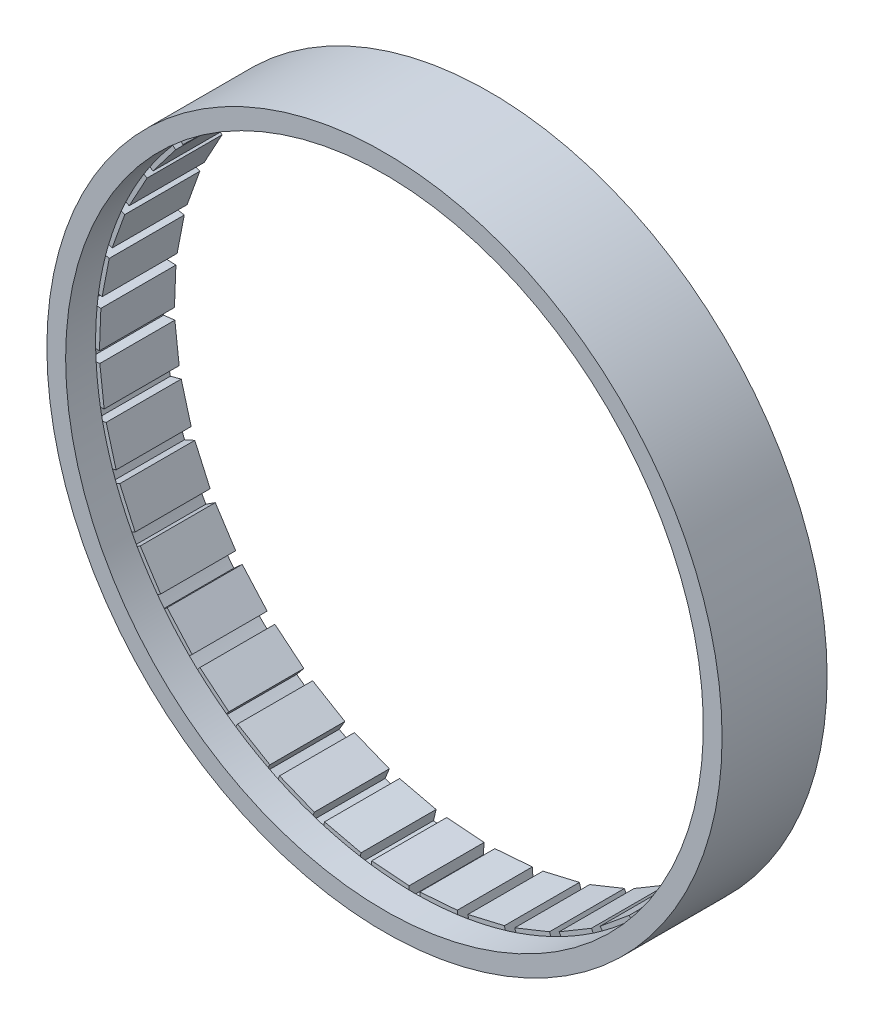
SolidWorks part; units mm, degrees
ref_plane "Front Plane" through (0, 0, 0) normal (0, 0, 1) x (1, 0, 0)
ref_plane "Top Plane" through (0, 0, 0) normal (0, 1, 0) x (1, 0, 0)
ref_plane "Right Plane" through (0, 0, 0) normal (1, 0, 0) x (0, 0, -1)
sketch "Sketch2" plane through (0, 0, 0) normal (1, 0, 0) x (0, 0, -1)
  line L0 (0, 0) -> (-98.2666, 0) construction
  line L1 (0, 45) -> (-14, 45)
  line L2 (-14, 45) -> (-14, 42.5)
  line L3 (-14, 42.5) -> (-10, 42.5)
  line L4 (-10, 42.5) -> (-10, 43.5)
  line L5 (-10, 43.5) -> (0, 43.5)
  line L6 (0, 43.5) -> (0, 45)
  point P5 (-13.7995, 43.5307)
  dimension "D1" = 90
  dimension "D2" = 85
  dimension "D3" = 14
  dimension "D4" = 4
  dimension "D5" = 1.5
revolve "Revolve1" add sketch "Sketch2" angle 360 about L0
sketch "Sketch4" plane through (0, 0, 0) normal (0, 0, -1) x (-1, 0, 0)
  line L0 (-2.5, 41.9281) -> (2.5, 41.9281)
  line L1 (2.5, 41.9281) -> (2.5, 43.4281)
  line L2 (-2.5, 41.9281) -> (-2.5, 43.4281)
  line L3 (3.9296, 41.8183) -> (4.1586, 43.3008)
  line L4 (8.871, 41.0551) -> (9.1, 42.5375)
  line L5 (3.9296, 41.8183) -> (8.871, 41.0551)
  line L6 (10.2671, 40.7284) -> (10.7197, 42.1585)
  line L7 (15.0341, 39.2198) -> (15.4866, 40.6499)
  line L8 (10.2671, 40.7284) -> (15.0341, 39.2198)
  line L9 (16.3639, 38.6838) -> (17.0295, 40.0281)
  line L10 (20.8447, 36.4652) -> (21.5103, 37.8095)
  line L11 (16.3639, 38.6838) -> (20.8447, 36.4652)
  line L12 (22.0772, 35.7325) -> (22.9402, 36.9594)
  line L13 (26.1668, 32.8559) -> (27.0298, 34.0828)
  line L14 (22.0772, 35.7325) -> (26.1668, 32.8559)
  line L15 (27.273, 31.9437) -> (28.3132, 33.0245)
  line L16 (30.8756, 28.4765) -> (31.9158, 29.5573)
  line L17 (27.273, 31.9437) -> (30.8756, 28.4765)
  line L18 (31.8296, 27.4061) -> (33.0225, 28.3155)
  line L19 (34.8607, 23.4296) -> (36.0536, 24.339)
  line L20 (31.8296, 27.4061) -> (34.8607, 23.4296)
  line L21 (35.6401, 22.2262) -> (36.9578, 22.9427)
  line L22 (38.0287, 17.8336) -> (39.3464, 18.5502)
  line L23 (35.6401, 22.2262) -> (38.0287, 17.8336)
  line L24 (38.6152, 16.5253) -> (40.0269, 17.0323)
  line L25 (40.3053, 11.8196) -> (41.717, 12.3266)
  line L26 (38.6152, 16.5253) -> (40.3053, 11.8196)
  line L27 (40.6852, 10.437) -> (42.1578, 10.7226)
  line L28 (41.6371, 5.5285) -> (43.1097, 5.8141)
  line L29 (40.6852, 10.437) -> (41.6371, 5.5285)
  line L30 (41.8016, 4.1041) -> (43.3005, 4.1616)
  line L31 (41.9931, -0.8922) -> (43.492, -0.8348)
  line L32 (41.8016, 4.1041) -> (41.9931, -0.8922)
  line L33 (41.9382, -2.325) -> (43.4283, -2.497)
  line L34 (41.3648, -7.292) -> (42.8549, -7.464)
  line L35 (41.9382, -2.325) -> (41.3648, -7.292)
  line L36 (41.0918, -8.6995) -> (42.5382, -9.097)
  line L37 (39.7669, -13.5208) -> (41.2132, -13.9183)
  line L38 (41.0918, -8.6995) -> (39.7669, -13.5208)
  line L39 (39.2822, -14.8702) -> (40.651, -15.4838)
  line L40 (37.2369, -19.4327) -> (38.6056, -20.0463)
  line L41 (39.2822, -14.8702) -> (37.2369, -19.4327)
  line L42 (36.5519, -20.6923) -> (37.811, -21.5077)
  line L43 (33.8341, -24.8892) -> (35.0931, -25.7045)
  line L44 (36.5519, -20.6923) -> (33.8341, -24.8892)
  line L45 (32.9649, -26.0295) -> (34.0847, -27.0274)
  line L46 (29.6382, -29.7622) -> (30.7581, -30.7602)
  line L47 (32.9649, -26.0295) -> (29.6382, -29.7622)
  line L48 (28.6052, -30.7565) -> (29.5595, -31.9137)
  line L49 (24.7477, -33.9377) -> (25.7021, -35.0949)
  line L50 (28.6052, -30.7565) -> (24.7477, -33.9377)
  line L51 (23.575, -34.7626) -> (24.3415, -36.0519)
  line L52 (19.2771, -37.3177) -> (20.0436, -38.607)
  line L53 (23.575, -34.7626) -> (19.2771, -37.3177)
  line L54 (17.9922, -37.9539) -> (18.5529, -39.3451)
  line L55 (13.3547, -39.823) -> (13.9154, -41.2142)
  line L56 (17.9922, -37.9539) -> (13.3547, -39.823)
  line L57 (11.9877, -40.2556) -> (12.3295, -41.7161)
  line L58 (7.1192, -41.3948) -> (7.461, -42.8554)
  line L59 (11.9877, -40.2556) -> (7.1192, -41.3948)
  line L60 (5.7022, -41.6137) -> (5.8171, -43.1093)
  line L61 (0.7169, -41.9964) -> (0.8317, -43.492)
  line L62 (5.7022, -41.6137) -> (0.7169, -41.9964)
  line L63 (-0.7169, -41.9964) -> (-0.8317, -43.492)
  line L64 (-5.7022, -41.6137) -> (-5.8171, -43.1093)
  line L65 (-0.7169, -41.9964) -> (-5.7022, -41.6137)
  line L66 (-7.1192, -41.3948) -> (-7.461, -42.8554)
  line L67 (-11.9877, -40.2556) -> (-12.3295, -41.7161)
  line L68 (-7.1192, -41.3948) -> (-11.9877, -40.2556)
  line L69 (-13.3547, -39.823) -> (-13.9154, -41.2142)
  line L70 (-17.9922, -37.9539) -> (-18.5529, -39.3451)
  line L71 (-13.3547, -39.823) -> (-17.9922, -37.9539)
  line L72 (-19.2771, -37.3177) -> (-20.0436, -38.607)
  line L73 (-23.575, -34.7626) -> (-24.3415, -36.0519)
  line L74 (-19.2771, -37.3177) -> (-23.575, -34.7626)
  line L75 (-24.7477, -33.9377) -> (-25.7021, -35.0949)
  line L76 (-28.6052, -30.7565) -> (-29.5595, -31.9137)
  line L77 (-24.7477, -33.9377) -> (-28.6052, -30.7565)
  line L78 (-29.6382, -29.7622) -> (-30.7581, -30.7602)
  line L79 (-32.9649, -26.0295) -> (-34.0847, -27.0274)
  line L80 (-29.6382, -29.7622) -> (-32.9649, -26.0295)
  line L81 (-33.8341, -24.8892) -> (-35.0931, -25.7045)
  line L82 (-36.5519, -20.6923) -> (-37.811, -21.5077)
  line L83 (-33.8341, -24.8892) -> (-36.5519, -20.6923)
  line L84 (-37.2369, -19.4327) -> (-38.6056, -20.0463)
  line L85 (-39.2822, -14.8702) -> (-40.651, -15.4838)
  line L86 (-37.2369, -19.4327) -> (-39.2822, -14.8702)
  line L87 (-39.7669, -13.5208) -> (-41.2132, -13.9183)
  line L88 (-41.0918, -8.6995) -> (-42.5382, -9.097)
  line L89 (-39.7669, -13.5208) -> (-41.0918, -8.6995)
  line L90 (-41.3648, -7.292) -> (-42.8549, -7.464)
  line L91 (-41.9382, -2.325) -> (-43.4283, -2.497)
  line L92 (-41.3648, -7.292) -> (-41.9382, -2.325)
  line L93 (-41.9931, -0.8922) -> (-43.492, -0.8348)
  line L94 (-41.8016, 4.1041) -> (-43.3005, 4.1616)
  line L95 (-41.9931, -0.8922) -> (-41.8016, 4.1041)
  line L96 (-41.6371, 5.5285) -> (-43.1097, 5.8141)
  line L97 (-40.6852, 10.437) -> (-42.1578, 10.7226)
  line L98 (-41.6371, 5.5285) -> (-40.6852, 10.437)
  line L99 (-40.3053, 11.8196) -> (-41.717, 12.3266)
  line L100 (-38.6152, 16.5253) -> (-40.0269, 17.0323)
  line L101 (-40.3053, 11.8196) -> (-38.6152, 16.5253)
  line L102 (-38.0287, 17.8336) -> (-39.3464, 18.5502)
  line L103 (-35.6401, 22.2262) -> (-36.9578, 22.9427)
  line L104 (-38.0287, 17.8336) -> (-35.6401, 22.2262)
  line L105 (-34.8607, 23.4296) -> (-36.0536, 24.339)
  line L106 (-31.8296, 27.4061) -> (-33.0225, 28.3155)
  line L107 (-34.8607, 23.4296) -> (-31.8296, 27.4061)
  line L108 (-30.8756, 28.4765) -> (-31.9158, 29.5573)
  line L109 (-27.273, 31.9437) -> (-28.3132, 33.0245)
  line L110 (-30.8756, 28.4765) -> (-27.273, 31.9437)
  line L111 (-26.1668, 32.8559) -> (-27.0298, 34.0828)
  line L112 (-22.0772, 35.7325) -> (-22.9402, 36.9594)
  line L113 (-26.1668, 32.8559) -> (-22.0772, 35.7325)
  line L114 (-20.8447, 36.4652) -> (-21.5103, 37.8095)
  line L115 (-16.3639, 38.6838) -> (-17.0295, 40.0281)
  line L116 (-20.8447, 36.4652) -> (-16.3639, 38.6838)
  line L117 (-15.0341, 39.2198) -> (-15.4866, 40.6499)
  line L118 (-10.2671, 40.7284) -> (-10.7197, 42.1585)
  line L119 (-15.0341, 39.2198) -> (-10.2671, 40.7284)
  line L120 (-8.871, 41.0551) -> (-9.1, 42.5375)
  line L121 (-3.9296, 41.8183) -> (-4.1586, 43.3008)
  line L122 (-8.871, 41.0551) -> (-3.9296, 41.8183)
  arc A0 (-2.5, 43.4281) -> (2.5, 43.4281) centre (0, 0) cw
  circle A1 centre (0, 0) radius 43.5 construction
  arc A2 (4.1586, 43.3008) -> (9.1, 42.5375) centre (0, 0) cw
  arc A3 (10.7197, 42.1585) -> (15.4866, 40.6499) centre (0, 0) cw
  arc A4 (17.0295, 40.0281) -> (21.5103, 37.8095) centre (0, 0) cw
  arc A5 (22.9402, 36.9594) -> (27.0298, 34.0828) centre (0, 0) cw
  arc A6 (28.3132, 33.0245) -> (31.9158, 29.5573) centre (0, 0) cw
  arc A7 (33.0225, 28.3155) -> (36.0536, 24.339) centre (0, 0) cw
  arc A8 (36.9578, 22.9427) -> (39.3464, 18.5502) centre (0, 0) cw
  arc A9 (40.0269, 17.0323) -> (41.717, 12.3266) centre (0, 0) cw
  arc A10 (42.1578, 10.7226) -> (43.1097, 5.8141) centre (0, 0) cw
  arc A11 (43.3005, 4.1616) -> (43.492, -0.8348) centre (0, 0) cw
  arc A12 (43.4283, -2.497) -> (42.8549, -7.464) centre (0, 0) cw
  arc A13 (42.5382, -9.097) -> (41.2132, -13.9183) centre (0, 0) cw
  arc A14 (40.651, -15.4838) -> (38.6056, -20.0463) centre (0, 0) cw
  arc A15 (37.811, -21.5077) -> (35.0931, -25.7045) centre (0, 0) cw
  arc A16 (34.0847, -27.0274) -> (30.7581, -30.7602) centre (0, 0) cw
  arc A17 (29.5595, -31.9137) -> (25.7021, -35.0949) centre (0, 0) cw
  arc A18 (24.3415, -36.0519) -> (20.0436, -38.607) centre (0, 0) cw
  arc A19 (18.5529, -39.3451) -> (13.9154, -41.2142) centre (0, 0) cw
  arc A20 (12.3295, -41.7161) -> (7.461, -42.8554) centre (0, 0) cw
  arc A21 (5.8171, -43.1093) -> (0.8317, -43.492) centre (0, 0) cw
  arc A22 (-0.8317, -43.492) -> (-5.8171, -43.1093) centre (0, 0) cw
  arc A23 (-7.461, -42.8554) -> (-12.3295, -41.7161) centre (0, 0) cw
  arc A24 (-13.9154, -41.2142) -> (-18.5529, -39.3451) centre (0, 0) cw
  arc A25 (-20.0436, -38.607) -> (-24.3415, -36.0519) centre (0, 0) cw
  arc A26 (-25.7021, -35.0949) -> (-29.5595, -31.9137) centre (0, 0) cw
  arc A27 (-30.7581, -30.7602) -> (-34.0847, -27.0274) centre (0, 0) cw
  arc A28 (-35.0931, -25.7045) -> (-37.811, -21.5077) centre (0, 0) cw
  arc A29 (-38.6056, -20.0463) -> (-40.651, -15.4838) centre (0, 0) cw
  arc A30 (-41.2132, -13.9183) -> (-42.5382, -9.097) centre (0, 0) cw
  arc A31 (-42.8549, -7.464) -> (-43.4283, -2.497) centre (0, 0) cw
  arc A32 (-43.492, -0.8348) -> (-43.3005, 4.1616) centre (0, 0) cw
  arc A33 (-43.1097, 5.8141) -> (-42.1578, 10.7226) centre (0, 0) cw
  arc A34 (-41.717, 12.3266) -> (-40.0269, 17.0323) centre (0, 0) cw
  arc A35 (-39.3464, 18.5502) -> (-36.9578, 22.9427) centre (0, 0) cw
  arc A36 (-36.0536, 24.339) -> (-33.0225, 28.3155) centre (0, 0) cw
  arc A37 (-31.9158, 29.5573) -> (-28.3132, 33.0245) centre (0, 0) cw
  arc A38 (-27.0298, 34.0828) -> (-22.9402, 36.9594) centre (0, 0) cw
  arc A39 (-21.5103, 37.8095) -> (-17.0295, 40.0281) centre (0, 0) cw
  arc A40 (-15.4866, 40.6499) -> (-10.7197, 42.1585) centre (0, 0) cw
  arc A41 (-9.1, 42.5375) -> (-4.1586, 43.3008) centre (0, 0) cw
  point P171 (0, 0)
  dimension "D1" = 5
  dimension "D2" = 1.5
  dimension "D3" = 41
extrude "Boss-Extrude1" add sketch "Sketch4" against normal up to surface (10 mm away) up to face at (-43.5, 0, 10)
